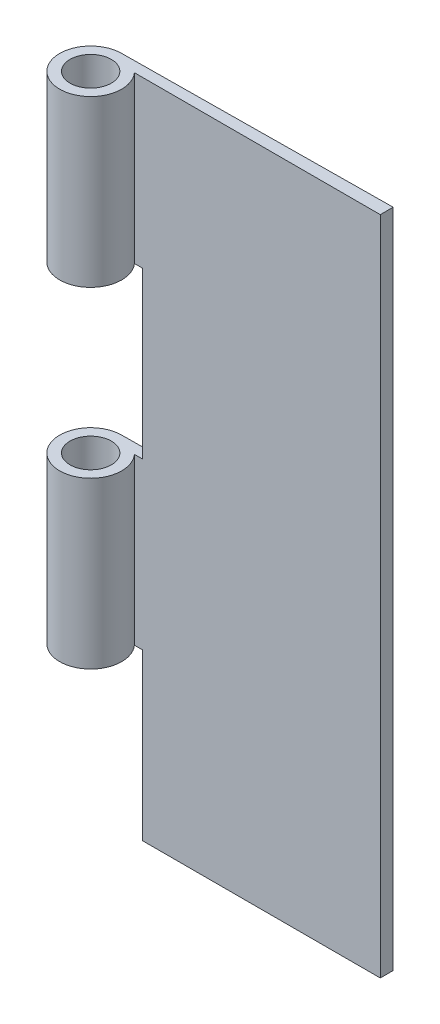
SolidWorks part; units mm, degrees
ref_plane "Front Plane" through (0, 0, 0) normal (0, 0, 1) x (1, 0, 0)
ref_plane "Top Plane" through (0, 0, 0) normal (0, 1, 0) x (1, 0, 0)
ref_plane "Right Plane" through (0, 0, 0) normal (1, 0, 0) x (0, 0, -1)
other "Configuration Table"
sketch "Sketch1" plane through (0, 0, 0) normal (0, 1, 0) x (1, 0, 0)
  circle A0 centre (130.0525, -2.7536) radius 7.5
  circle A1 centre (130.0525, -2.7536) radius 5
  dimension "D1" = 10
  dimension "D2" = 15
extrude "Boss-Extrude1" add sketch "Sketch1" along normal mid plane 160 contours A1
sketch "Sketch2" plane through (0, 80, 0) normal (0, 1, 0) x (1, 0, 0)
  line L0 (130.0525, 4.7464) -> (195.141, 5.3613)
  line L1 (130.0525, 4.7464) -> (130.0525, 2.2464)
  line L2 (130.0525, 2.2464) -> (195.141, 2.2464)
  line L3 (195.141, 2.2464) -> (195.141, 5.3613)
  circle A0 centre (130.0525, -2.7536) radius 7.5 construction
  circle A1 centre (130.0525, -2.7536) radius 5 construction
extrude "Boss-Extrude2" add sketch "Sketch2" against normal blind 160
sketch "Sketch3" plane through (0, 0, -2.2464) normal (0, 0, 1) x (1, 0, 0)
  line L0 (101.024, 40) -> (137.5525, 40)
  line L1 (137.5525, 40) -> (137.5525, 0)
  line L2 (137.5525, 0) -> (107.5991, 0)
  line L3 (107.5991, 0) -> (107.5991, -40)
  line L4 (107.5991, -40) -> (137.5525, -40)
  line L5 (137.5525, -40) -> (137.5525, -90)
  line L6 (137.5525, -90) -> (101.024, -90)
  line L7 (101.024, -90) -> (101.024, 40)
  line L8 (135.6426, 80) -> (195.141, 80) construction
  line L9 (137.5525, -80) -> (137.5525, 80) construction
  dimension "D1" = 40
  dimension "D2" = 40
  dimension "D3" = 50
  dimension "D4" = 40
  dimension "D5" = 0
extrude "Cut-Extrude1" cut sketch "Sketch3" against normal through all both and the other way through all
